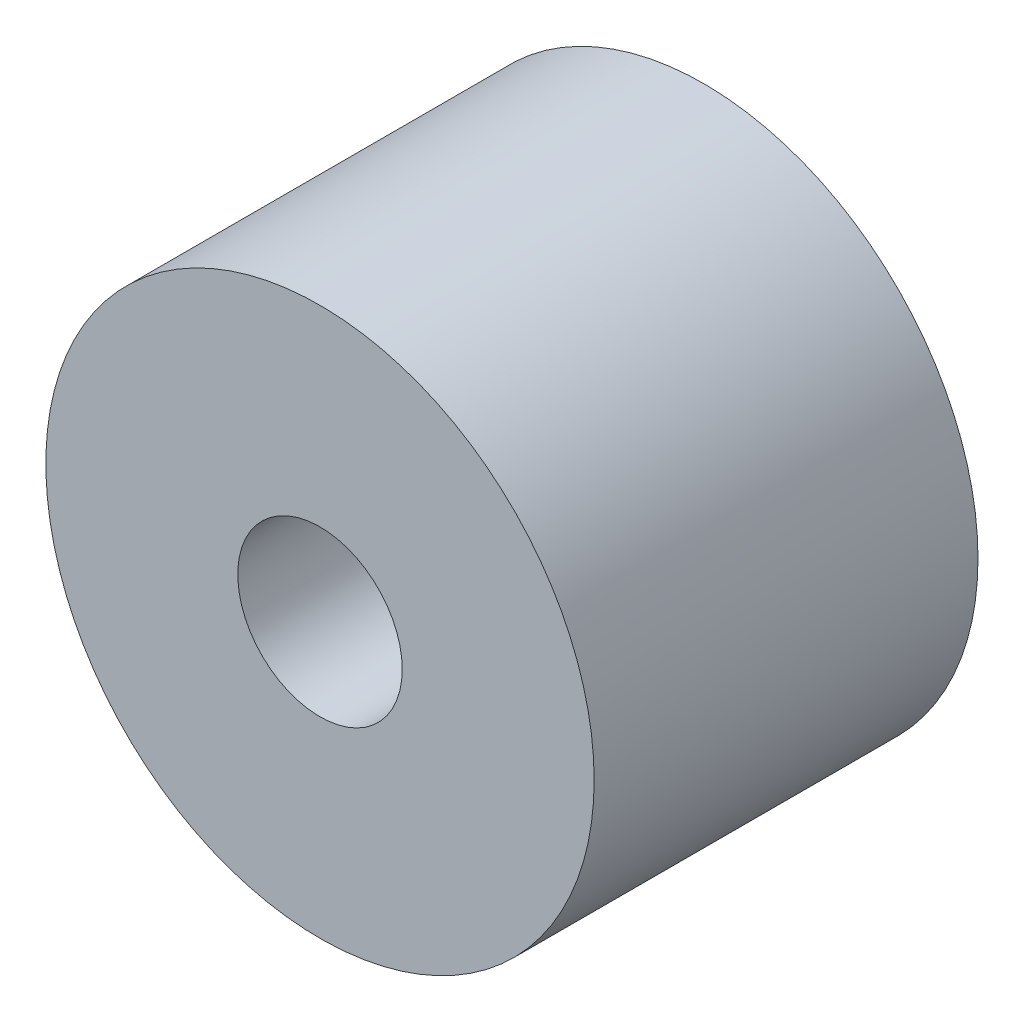
SolidWorks part; units mm, degrees
material "Силиконовая резина"
ref_plane "Спереди" through (0, 0, 0) normal (0, 0, 1) x (1, 0, 0)
ref_plane "Сверху" through (0, 0, 0) normal (0, 1, 0) x (1, 0, 0)
ref_plane "Справа" through (0, 0, 0) normal (1, 0, 0) x (0, 0, -1)
sketch "Эскиз1" plane through (0, 0, 0) normal (0, 0, 1) x (1, 0, 0)
  circle A0 centre (0, 0) radius 5
  circle A1 centre (0, 0) radius 1.5
  dimension "D1" = 3
  dimension "D2" = 10
extrude "База" add sketch "Эскиз1" along normal mid plane 7
